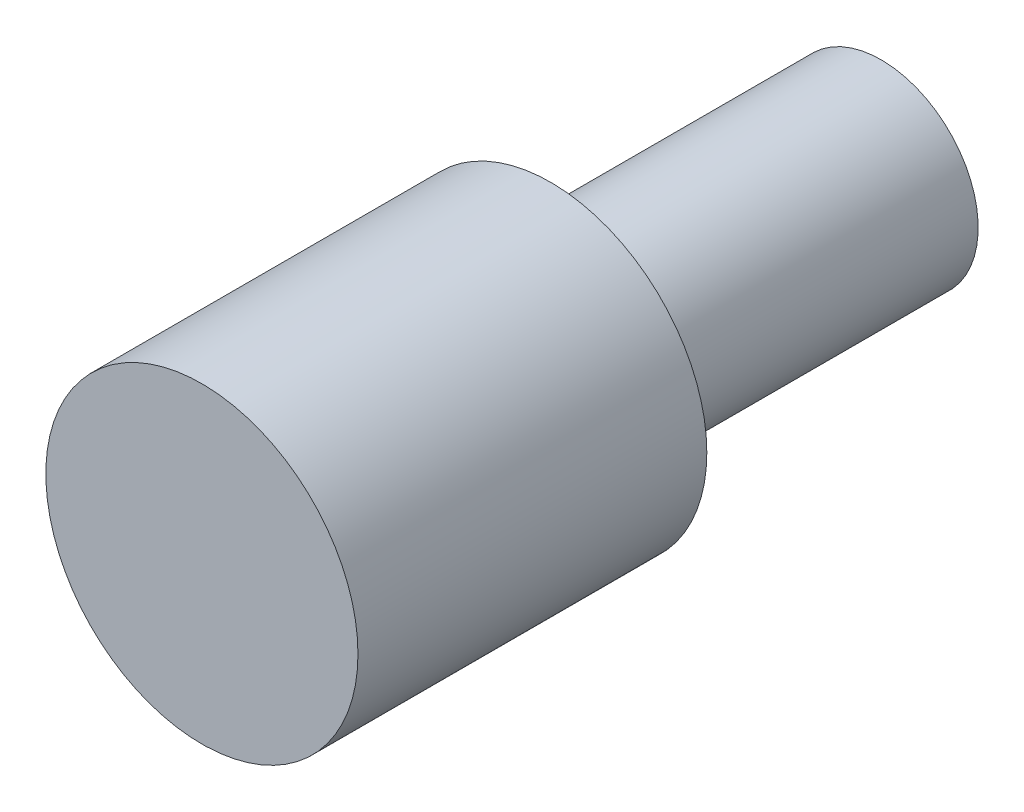
SolidWorks part; units mm, degrees
ref_plane "前视基准面" through (0, 0, 0) normal (0, 0, 1) x (1, 0, 0)
ref_plane "上视基准面" through (0, 0, 0) normal (0, 1, 0) x (1, 0, 0)
ref_plane "右视基准面" through (0, 0, 0) normal (1, 0, 0) x (0, 0, -1)
sketch "草图1" plane through (0, 0, 0) normal (0, 0, 1) x (1, 0, 0)
  circle A0 centre (0, 0) radius 7.65
  dimension "D1" = 15.3
extrude "凸台-拉伸1" add sketch "草图1" along normal blind 17.1
sketch "草图3" plane through (0, 0, 0) normal (0, 0, -1) x (-1, 0, 0)
  circle A0 centre (0, 0) radius 4.75
  dimension "D1" = 9.5
extrude "凸台-拉伸2" add sketch "草图3" along normal blind 16.2
sketch "草图4" plane through (0, 0, -16.2) normal (0, 0, -1) x (-1, 0, 0)
  circle A0 centre (0, 0) radius 3.5
  dimension "D1" = 7
extrude "切除-拉伸1" cut sketch "草图4" against normal blind 16.2
